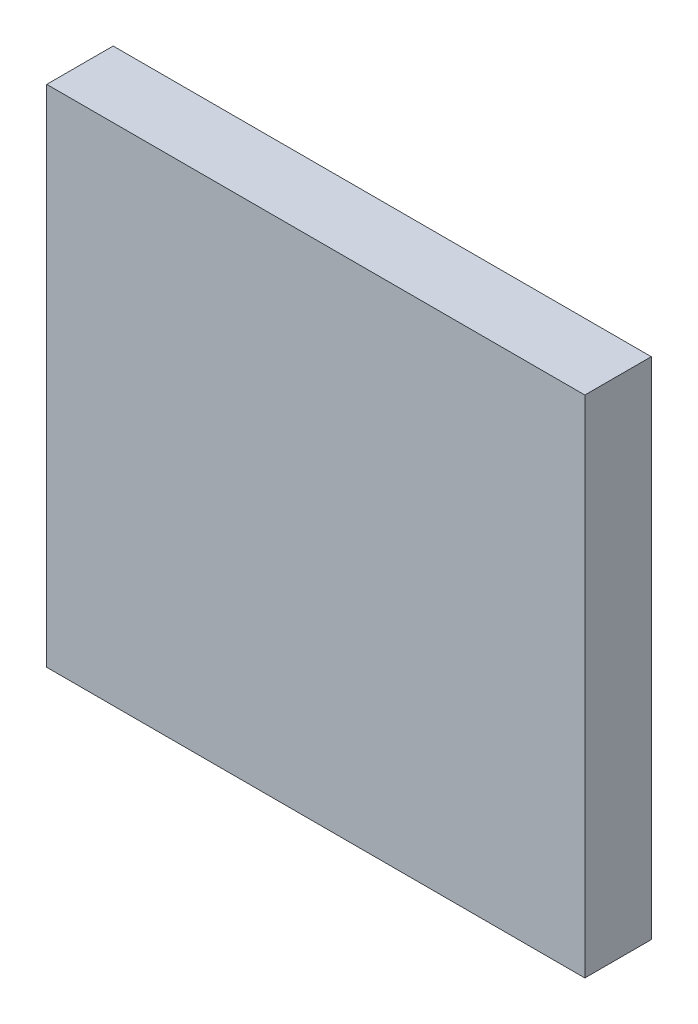
SolidWorks part; units mm, degrees
ref_plane "Front Plane" through (0, 0, 0) normal (0, 0, 1) x (1, 0, 0)
ref_plane "Top Plane" through (0, 0, 0) normal (0, 1, 0) x (1, 0, 0)
ref_plane "Right Plane" through (0, 0, 0) normal (1, 0, 0) x (0, 0, -1)
sketch "Sketch1" plane through (0, 0, 0) normal (0, 0, 1) x (1, 0, 0)
  line L0 (-4.1016, 3) -> (4, 3)
  line L1 (4, 3) -> (4, -4.6016)
  line L2 (4, -4.6016) -> (-4.1016, -4.6016)
  line L3 (-4.1016, -4.6016) -> (-4.1016, 3)
extrude "Component_Outline" add sketch "Sketch1" along normal blind 1 separate body
sketch3d "3DSketch1"
  line L0 (0, 0, 0) -> (1, 0, 0)
  line L1 (0, 0, 0) -> (0, 1, 0)
  line L2 (0, 0, 0) -> (0, 0, 1)
  point P0 (0, 0, 0)
